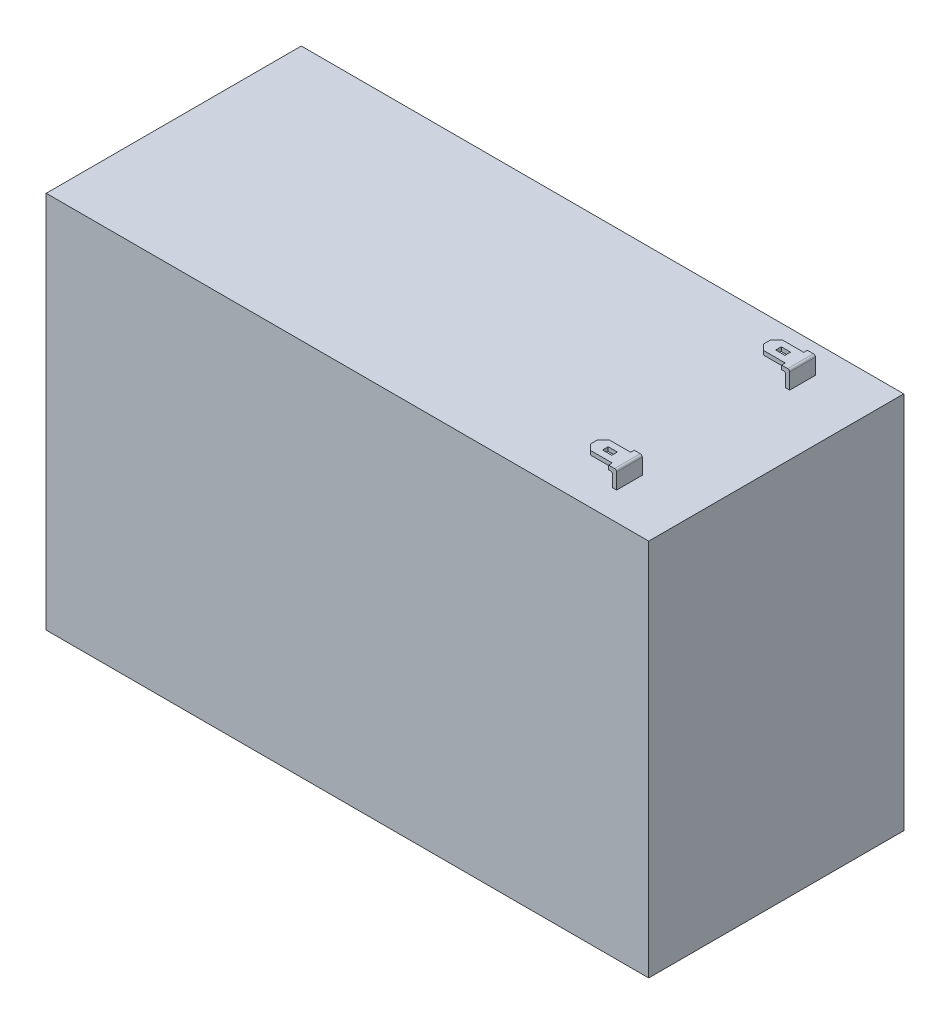
SolidWorks part; units mm, degrees
ref_plane "Front Plane" through (0, 0, 0) normal (0, 0, 1) x (1, 0, 0)
ref_plane "Top Plane" through (0, 0, 0) normal (0, 1, 0) x (1, 0, 0)
ref_plane "Right Plane" through (0, 0, 0) normal (1, 0, 0) x (0, 0, -1)
sketch "Sketch1" plane through (0, 0, 0) normal (0, 1, 0) x (1, 0, 0)
  line L1 (0, 0) -> (150, 0)
  line L2 (0, 0) -> (0, 63.5)
  line L3 (0, 63.5) -> (150, 63.5)
  line L4 (150, 0) -> (150, 63.5)
  dimension "D1" = 150
  dimension "D2" = 63.5
extrude "Boss-Extrude1" add sketch "Sketch1" along normal blind 94.2
ref_plane "Plane1" through (0, 0, -31.75) normal (0, 0, 1) x (1, 0, 0)
sketch "Sketch3" plane through (0, 94.2, 0) normal (0, 1, 0) x (1, 0, 0)
  line L0 (135, 7) -> (135, 56.5) construction
  line L1 (-51.81, 31.75) -> (51.81, 31.75) construction
  line L2 (150, 0) -> (150, 63.5) construction
  line L3 (135, 7) -> (135, 13.4)
  line L4 (135, 7) -> (133, 7)
  line L5 (126.2, 9.3) -> (126.2, 11.1)
  line L6 (133, 13.4) -> (135, 13.4)
  line L7 (127.6, 7.9) -> (133, 7.9)
  line L8 (133, 7.9) -> (133, 7)
  line L9 (127.6, 12.5) -> (133, 12.5)
  line L10 (133, 12.5) -> (133, 13.4)
  line L11 (126.2, 11.1) -> (127.6, 12.5)
  line L12 (131.3, 9.5) -> (129, 9.5)
  line L13 (131.3, 9.5) -> (131.3, 10.9)
  line L14 (131.3, 10.9) -> (129, 10.9)
  line L15 (129, 9.5) -> (129, 10.9)
  line L16 (126.2, 9.3) -> (127.6, 7.9)
  point P4 (135, 31.75)
  point P7 (126.2, 7.9)
  point P9 (126.2, 12.5)
  point P22 (131.3, 10.2)
  point P23 (135, 10.2)
  dimension "D1" = 49.5
  dimension "D2" = 15
  dimension "D3" = 6.4
  dimension "D4" = 8.8
  dimension "D5" = 0.9
  dimension "D6" = 2
  dimension "D7" = 0.9
  dimension "D8" = 1.4
  dimension "D9" = 2.3
  dimension "D10" = 2.8
extrude "Boss-Extrude2" add sketch "Sketch3" along normal blind 4.4
sketch "Sketch4" plane through (0, 0, -7) normal (0, 0, 1) x (1, 0, 0)
  line L0 (135, 94.2) -> (135, 98.1)
  line L1 (134.5, 98.6) -> (126.2, 98.6)
  line L2 (126.2, 98.6) -> (126.2, 97.6)
  line L3 (126.2, 98.6) -> (126.2, 94.2) construction
  line L4 (126.2, 97.6) -> (133.5, 97.6)
  line L5 (134, 97.1) -> (134, 94.2)
  line L6 (0, 94.2) -> (150, 94.2) construction
  line L7 (134, 94.2) -> (135, 94.2)
  line L8 (126.2, 97.6) -> (126.2, 94.2)
  line L9 (126.2, 94.2) -> (134, 94.2)
  line L10 (134.5, 98.6) -> (135, 98.6)
  line L11 (135, 98.6) -> (135, 98.1)
  arc A0 (134, 97.1) -> (133.5, 97.6) centre (133.5, 97.1) ccw
  arc A1 (135, 98.1) -> (134.5, 98.6) centre (134.5, 98.1) ccw
  point P19 (135, 98.6)
  line M9 (133, 94.2) -> (135, 94.2)
  line M10 (135, 94.2) -> (135, 98.6)
  line M11 (135, 98.6) -> (133, 98.6)
  line M12 (133, 98.6) -> (133, 94.2)
  dimension "D3" = 0.5
  dimension "D1" = 1
  dimension "D2" = 1
extrude "Cut-Extrude1" cut sketch "Sketch4" against normal through all contours L8 L9 L4 M12 | L5 A0 L4 M12 M9 | A1 M10 M11
mirror "Mirror1" about plane through (0, 0, -31.75) normal (0, 0, 1) of "Cut-Extrude1", "Boss-Extrude2"
ref_plane "Plane2" through (75, 0, 0) normal (-1, 0, 0) x (0, 0, 1)
